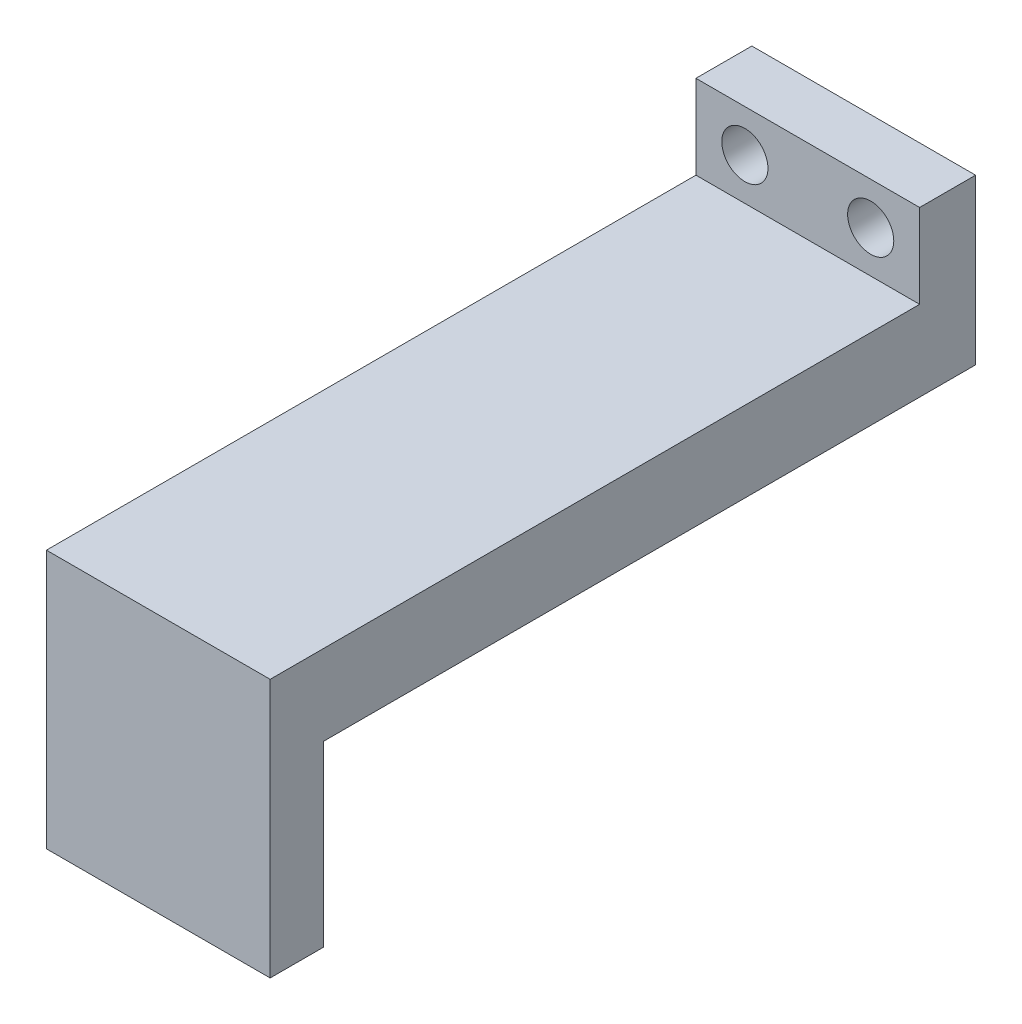
SolidWorks part; units mm, degrees
ref_plane "前视基准面" through (0, 0, 0) normal (0, 0, 1) x (1, 0, 0)
ref_plane "上视基准面" through (0, 0, 0) normal (0, 1, 0) x (1, 0, 0)
ref_plane "右视基准面" through (0, 0, 0) normal (1, 0, 0) x (0, 0, -1)
other "Configuration Table"
sketch "Bracket foot profile" plane through (0, 0, 0) normal (0, 0, 1) x (1, 0, 0)
  line L0 (-8, 27.25) -> (8, 27.25)
  line L1 (8, 27.25) -> (8, 39)
  line L2 (8, 39) -> (-8, 39)
  line L3 (-8, 39) -> (-8, 27.25)
extrude "Bracket foot" add sketch "Bracket foot profile" along normal blind 4
sketch "Upright profile" plane through (0, 0, 0) normal (0, 0, 1) x (1, 0, 0)
  line L0 (-8, 27.25) -> (8, 27.25)
  line L1 (8, 27.25) -> (8, 33)
  line L2 (8, 33) -> (-8, 33)
  line L3 (-8, 33) -> (-8, 27.25)
extrude "Upright" add sketch "Upright profile" along normal blind 46.45 from offset 4
sketch "Upper arm profile" plane through (0, 0, 0) normal (0, 0, 1) x (1, 0, 0)
  line L0 (-8, 14.5) -> (8, 14.5)
  line L1 (8, 14.5) -> (8, 27.7)
  line L2 (8, 27.7) -> (-8, 27.7)
  line L3 (-8, 27.7) -> (-8, 14.5)
extrude "Upper arm" add sketch "Upper arm profile" along normal blind 3.8 from offset 46.65
sketch "Bracket bolt clearances profile" plane through (0, 0, 0) normal (0, 0, 1) x (1, 0, 0)
  circle A0 centre (-4.5, 36) radius 1.65
  circle A1 centre (4.5, 36) radius 1.65
extrude "Bracket bolt clearances" cut sketch "Bracket bolt clearances profile" along normal blind 4.2 from offset 0.1
sketch "Integral stop pin diameter 4 mm profile" plane through (0, 0, 0) normal (0, 0, 1) x (1, 0, 0)
  circle A0 centre (0, 17) radius 2
extrude "Integral stop pin diameter 4 mm" add sketch "Integral stop pin diameter 4 mm profile" along normal blind 3.5 from offset 43.35
